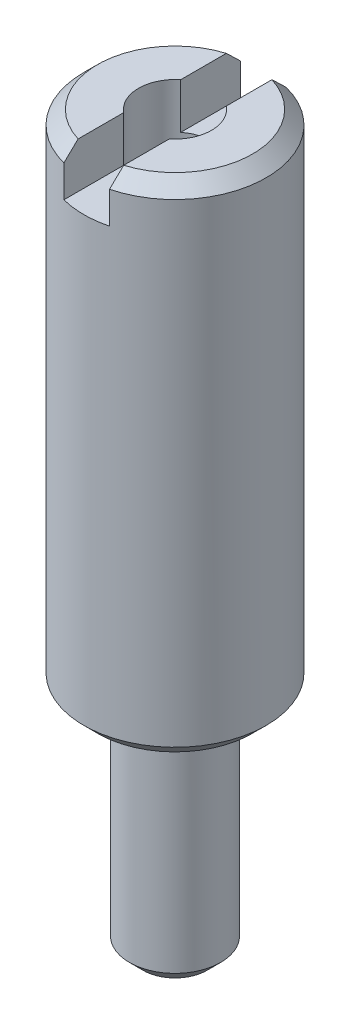
SolidWorks part; units mm, degrees
material "A2017"
ref_plane "正面" through (0, 0, 0) normal (0, 0, 1) x (1, 0, 0)
ref_plane "平面" through (0, 0, 0) normal (0, 1, 0) x (1, 0, 0)
ref_plane "右側面" through (0, 0, 0) normal (1, 0, 0) x (0, 0, -1)
sketch "ｽｹｯﾁ1" plane through (0, 0, 0) normal (0, 0, 1) x (1, 0, 0)
  line L0 (0, 16.0048) -> (0, -5) construction
  line L1 (0, -5) -> (-1, -5)
  line L2 (-1, -5) -> (-1, 0)
  line L3 (-1, 0) -> (-2, 0)
  line L4 (-2, 0) -> (-2, 11)
  line L5 (-2, 11) -> (0, 11)
  line L6 (0, -5) -> (0, 11)
  dimension "D1" = 2
  dimension "D2" = 5
  dimension "D3" = 11
  dimension "D4" = 4
revolve "回転1" add sketch "ｽｹｯﾁ1" angle 360 about L0
chamfer "面取り1" distance 0.3 angle 45 3 edges at (-2, 11, 0) (-2, 0, 0) (-1, -5, 0)
sketch "ｽｹｯﾁ2" plane through (0, 11, 0) normal (0, 1, 0) x (1, 0, 0)
  line L1 (0.5, -1.9365) -> (-0.5, -1.9365) construction
  line L2 (0.5, -1.9365) -> (0.5, 1.9365)
  line L3 (0.5, 1.9365) -> (-0.5, 1.9365) construction
  line L4 (-0.5, -1.9365) -> (-0.5, 1.9365)
  line L5 (0.5, -1.9365) -> (-0.5, 1.9365) construction
  line L6 (0.5, 1.9365) -> (-0.5, -1.9365) construction
  circle A0 centre (0, 0) radius 2 construction
  arc A1 (0.5, 1.9365) -> (-0.5, 1.9365) centre (0, 0) ccw
  arc A2 (-0.5, -1.9365) -> (0.5, -1.9365) centre (0, 0) ccw
  point P0 (0, 0)
  dimension "D1" = 1
extrude "ｶｯﾄ - 押し出し2" cut sketch "ｽｹｯﾁ2" against normal blind 1
hole_wizard "M2 ねじ穴1" positions "ｽｹｯﾁ3" profile "ｽｹｯﾁ4" tap size "M2" standard "JIS"
sketch "ｽｹｯﾁ3" plane through (0, 11, 0) normal (0, 1, 0) x (1, 0, 0)
  point P0 (0, 0)
sketch "ｽｹｯﾁ4" plane through (0, 11, 0) normal (1, 0, 0) x (0, 0, 1)
  line L0 (0, 0) -> (0, 8.4807)
  line L1 (0, 8.4807) -> (0.8, 8)
  line L2 (0.8, 8) -> (0.8, 0)
  line L5 (0.8, 0) -> (0, 0)
  line L10 (0, 8.4807) -> (-0.8, 8) construction
  line L11 (0, -6.35) -> (0, 107.95) construction
  dimension "ねじ下穴ﾄﾞﾘﾙ直径" = 1.6
  dimension "ねじ下穴ﾄﾞﾘﾙの深さ" = 8
  dimension "ﾄﾞﾘﾙ角度" = 118
cosmetic thread "穴のねじ山1"
